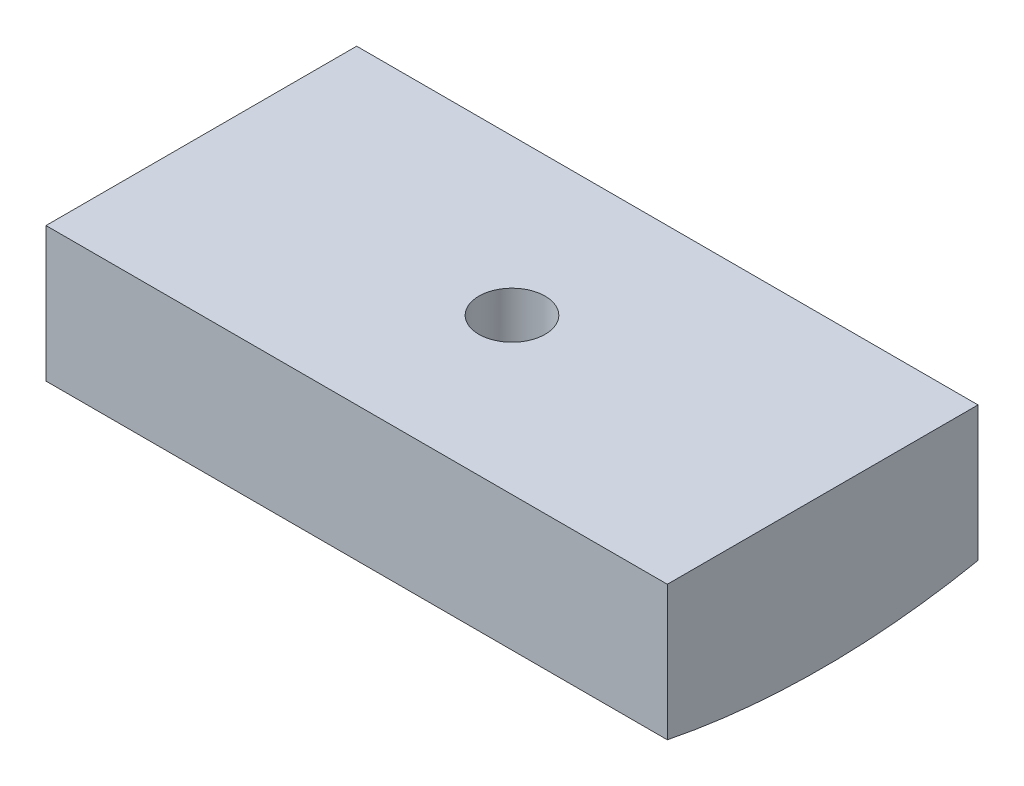
SolidWorks part; units mm, degrees
ref_plane "Front Plane" through (0, 0, 0) normal (0, 0, 1) x (1, 0, 0)
ref_plane "Top Plane" through (0, 0, 0) normal (0, 1, 0) x (1, 0, 0)
ref_plane "Right Plane" through (0, 0, 0) normal (1, 0, 0) x (0, 0, -1)
sketch "Sketch1" plane through (0, 0, 0) normal (1, 0, 0) x (0, 0, -1)
  line L0 (0, 0) -> (0, -90.5205) construction
  line L1 (-15, -61.79) -> (15, -61.79)
  line L2 (-15, -61.79) -> (-15, -74.8008)
  line L4 (15, -61.79) -> (15, -74.8008)
  arc A0 (-15, -74.8008) -> (15, -74.8008) centre (0, 0) ccw construction
  arc A1 (-15, -74.8008) -> (15, -74.8008) centre (0, 0) ccw
  circle A2 centre (0, 0) radius 76.29 construction
  point P7 (0, -76.29)
  dimension "D1" = 152.58
  dimension "D2" = 14.5
  dimension "D3" = 30
extrude "Boss-Extrude1" add sketch "Sketch1" along normal blind 60
sketch "Sketch2" plane through (0, -61.79, 0) normal (0, 1, 0) x (1, 0, 0)
  line L0 (0, 15) -> (60, -15) construction
  line L1 (0, -15) -> (60, 15) construction
  circle A0 centre (30, 0) radius 3.2
  dimension "D1" = 6.4
extrude "Cut-Extrude1" cut sketch "Sketch2" against normal through all
